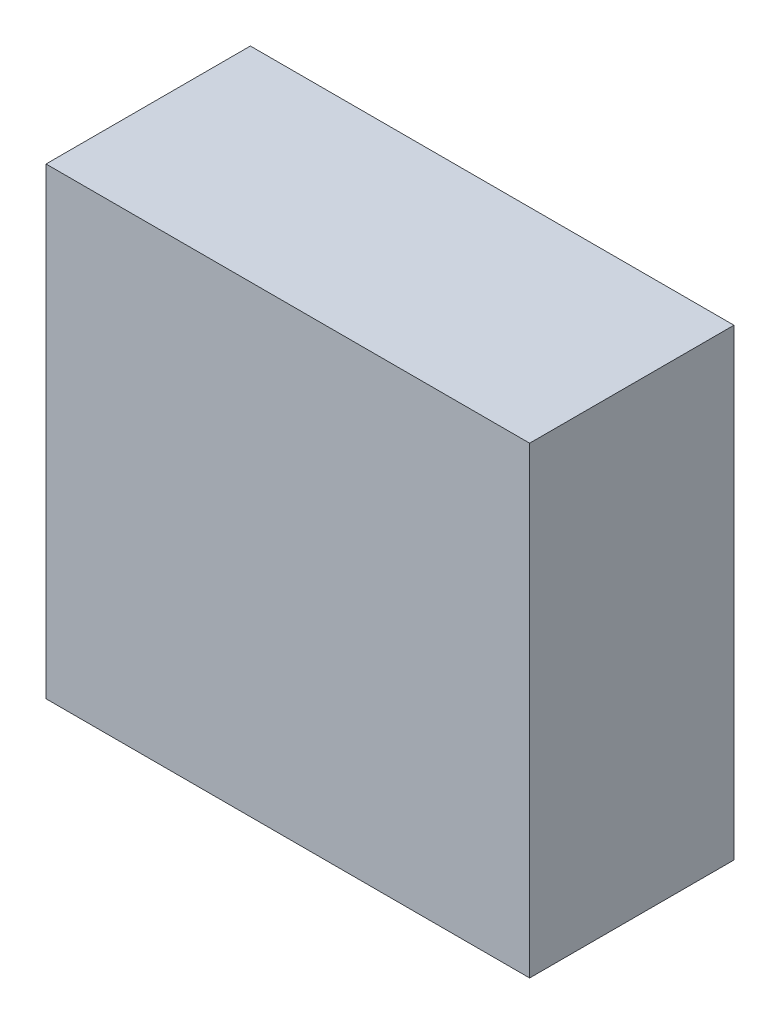
SolidWorks part; units mm, degrees
material "ABS"
ref_plane "Front Plane" through (0, 0, 0) normal (0, 0, 1) x (1, 0, 0)
ref_plane "Top Plane" through (0, 0, 0) normal (0, 1, 0) x (1, 0, 0)
ref_plane "Right Plane" through (0, 0, 0) normal (1, 0, 0) x (0, 0, -1)
sketch "Sketch1" plane through (0, 0, 0) normal (0, 1, 0) x (1, 0, 0)
  line L1 (-90.17, -38.1) -> (90.17, -38.1)
  line L2 (-90.17, -38.1) -> (-90.17, 38.1)
  line L3 (-90.17, 38.1) -> (90.17, 38.1)
  line L4 (90.17, -38.1) -> (90.17, 38.1)
  line L5 (-90.17, -38.1) -> (90.17, 38.1) construction
  line L6 (-90.17, 38.1) -> (90.17, -38.1) construction
  point P0 (0, 0)
  dimension "D1" = 76.2
  dimension "D2" = 180.34
extrude "Boss-Extrude1" add sketch "Sketch1" along normal blind 172.72
sketch "Sketch2" plane through (0, 172.72, 0) normal (0, 1, 0) x (1, 0, 0)
  line L0 (-90.17, -38.1) -> (90.17, 38.1) construction
  line L1 (-90.17, 38.1) -> (-90.17, -38.1) construction
  line L2 (-90.17, -38.1) -> (90.17, -38.1) construction
  line L3 (90.17, 38.1) -> (-90.17, 38.1) construction
  line L4 (90.17, -38.1) -> (90.17, 38.1) construction
  circle A0 centre (0, 0) radius 13.5342 construction
  dimension "D1" = 27.0684
